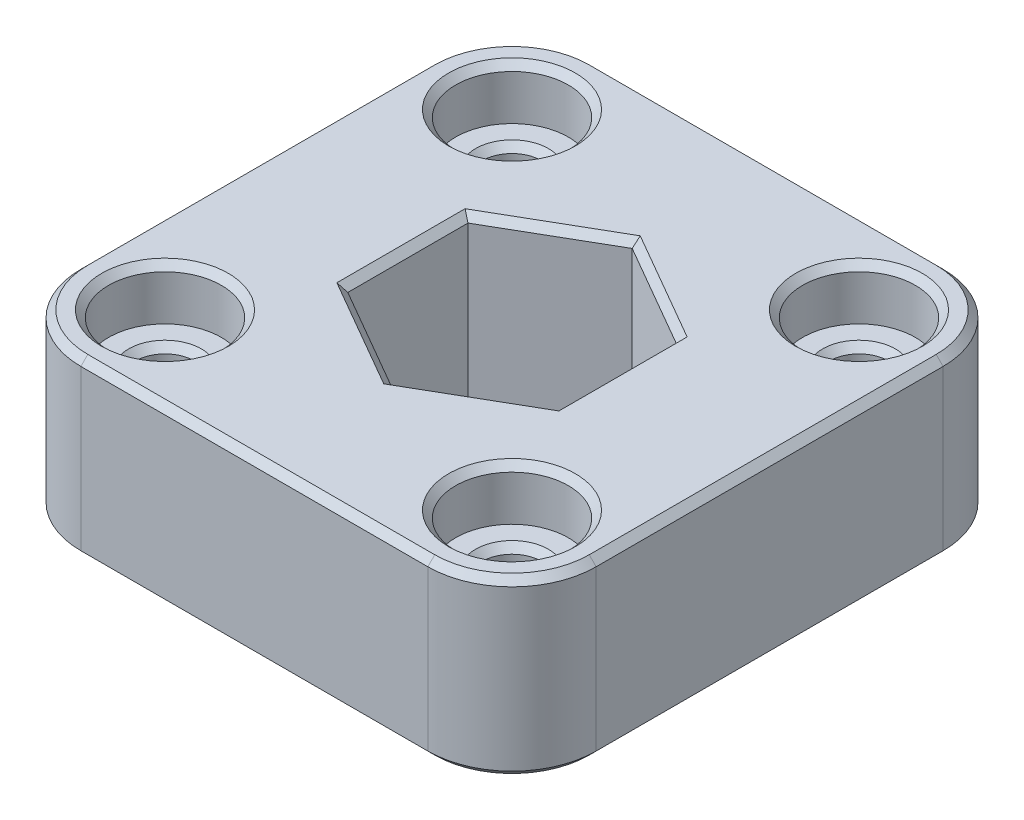
SolidWorks part; units mm, degrees
ref_plane "Front Plane" through (0, 0, 0) normal (0, 0, 1) x (1, 0, 0)
ref_plane "Top Plane" through (0, 0, 0) normal (0, 1, 0) x (1, 0, 0)
ref_plane "Right Plane" through (0, 0, 0) normal (1, 0, 0) x (0, 0, -1)
sketch "Sketch3" plane through (0, 0, 0) normal (0, 1, 0) x (1, 0, 0)
  line L0 (-14.85, -10) -> (-14.85, 10)
  line L1 (-6, 3.4641) -> (-6, -3.4641)
  line L2 (-6, -3.4641) -> (0, -6.9282)
  line L3 (0, -6.9282) -> (6, -3.4641)
  line L4 (6, -3.4641) -> (6, 3.4641)
  line L5 (6, 3.4641) -> (0, 6.9282)
  line L6 (0, 6.9282) -> (-6, 3.4641)
  line L7 (-10, 14.85) -> (10, 14.85)
  line L8 (14.85, 10) -> (14.85, -10)
  line L9 (10, -14.85) -> (-10, -14.85)
  circle A0 centre (0, 0) radius 6 construction
  arc A1 (-10, -14.85) -> (-14.85, -10) centre (-10, -10) cw
  arc A2 (14.85, -10) -> (10, -14.85) centre (10, -10) cw
  arc A3 (10, 14.85) -> (14.85, 10) centre (10, 10) cw
  arc A4 (-14.85, 10) -> (-10, 14.85) centre (-10, 10) cw
  circle A5 centre (-10, -10) radius 3.25 construction
  point P12 (-14.85, 0)
  point P22 (0, 14.85)
  dimension "D2" = 1.6
  dimension "D4" = 6.5
  dimension "D1" = 12
  dimension "D3" = 20
extrude "Boss-Extrude1" add sketch "Sketch3" along normal blind 10
hole_wizard "CBORE for M3 SHCS1" positions "Sketch4" profile "Sketch5" counterbore size "M3" standard "ANSI Metric" end condition through all
sketch "Sketch4" plane through (0, 10, 0) normal (0, 1, 0) x (1, 0, 0)
  point P0 (-10, 10)
  point P3 (10, 10)
  point P6 (10, -10)
  point P9 (-10, -10)
sketch "Sketch5" plane through (-10, 10, -10) normal (1, 0, 0) x (0, 0, 1)
  line L0 (0, 0) -> (0, 10)
  line L1 (1.7, 9.6) -> (2.1, 10)
  line L2 (1.7, 9.6) -> (1.7, 3.4)
  line L3 (1.7, 3.4) -> (2.1, 3)
  line L4 (2.1, 3) -> (3.25, 3)
  line L5 (3.25, 3) -> (3.25, 0.4)
  line L6 (3.25, 0.4) -> (3.65, 0)
  line L7 (3.65, 0) -> (0, 0)
  line L8 (-3.25, 0.4) -> (-3.65, 0) construction
  line L9 (-1.7, 3.4) -> (-2.1, 3) construction
  line L11 (0, -6.35) -> (0, 107.95) construction
  line L12 (2.1, 10) -> (0, 10)
  line L13 (-1.7, 9.6) -> (-2.1, 10) construction
  dimension "Thru Hole Dia." = 3.4
  dimension "Thru Hole Depth" = 10
  dimension "C'Bore Dia." = 6.5
  dimension "C'Bore Depth" = 3
  dimension "Near C'Sink Dia." = 7.3
  dimension "Near C'Sink Angle" = 90
  dimension "Mid C'Sink Dia." = 4.2
  dimension "Mid C'Sink Angle" = 90
  dimension "Far C'Sink Dia." = 4.2
  dimension "Far C'Sink Angle" = 90
chamfer "Chamfer1" distance 0.4 angle 45 28 edges at (-3, 0, 5.1962) (3, 0, 5.1962) (6, 0, 0) (3, 0, -5.1962) (-3, 0, -5.1962) (-6, 0, 0) (-14.85, 0, 0) (-13.4295, 0, 13.4295) (-13.4295, 0, -13.4295) (0, 0, 14.85) (0, 0, -14.85) (13.4295, 0, 13.4295) (13.4295, 0, -13.4295) (14.85, 0, 0) (-14.85, 10, 0) (-13.4295, 10, 13.4295) (-13.4295, 10, -13.4295) (0, 10, 14.85) (0, 10, -14.85) (13.4295, 10, 13.4295) (13.4295, 10, -13.4295) (14.85, 10, 0) (3, 10, 5.1962) (-3, 10, 5.1962) (-6, 10, 0) (6, 10, 0) (3, 10, -5.1962) (-3, 10, -5.1962)
